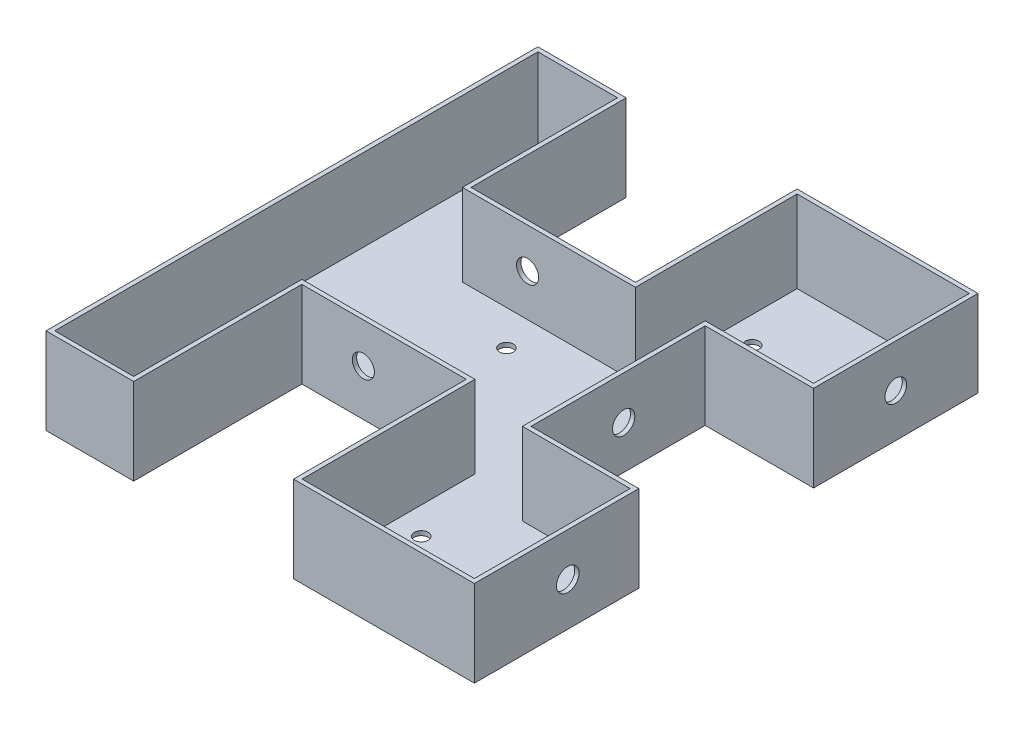
SolidWorks part; units mm, degrees
ref_plane "Front Plane" through (0, 0, 0) normal (0, 0, 1) x (1, 0, 0)
ref_plane "Top Plane" through (0, 0, 0) normal (0, 1, 0) x (1, 0, 0)
ref_plane "Right Plane" through (0, 0, 0) normal (1, 0, 0) x (0, 0, -1)
sketch "Sketch1" plane through (0, 0, 0) normal (0, 1, 0) x (1, 0, 0)
  line L0 (543.0661, -1022.739) -> (543.0661, -1018.5177)
  line L1 (574.7353, -1103.2077) -> (586.3832, -1103.2077) construction
  line L2 (543.0661, -1018.5177) -> (584.9761, -1018.5177)
  line L5 (584.9761, -1056.6177) -> (584.9761, -1018.5177)
  line L6 (559.8652, -1056.6177) -> (584.9761, -1056.6177)
  line L7 (584.8424, -1103.2077) -> (584.8424, -1096.9737)
  line L9 (584.8424, -1096.9737) -> (559.8652, -1096.9737)
  line L10 (559.8652, -1096.9737) -> (559.8652, -1056.6177)
  line L11 (584.8424, -1103.2077) -> (584.8424, -1135.0737)
  line L12 (542.9324, -1128.2718) -> (542.9324, -1135.0737)
  line L14 (542.9324, -1135.0737) -> (584.8424, -1135.0737)
  line L15 (542.9324, -1128.2718) -> (542.9324, -1095.0332)
  line L16 (542.9324, -1095.0332) -> (504.8324, -1095.0332)
  line L17 (504.8324, -1095.0332) -> (504.8324, -1128.2718)
  line L18 (504.8324, -1128.2718) -> (504.8324, -1133.9991)
  line L20 (504.8324, -1133.9991) -> (484.5124, -1133.9991)
  line L21 (484.5124, -1133.9991) -> (484.5124, -1020.0236)
  line L23 (504.9661, -1022.739) -> (504.9661, -1020.0236)
  line L24 (484.5124, -1020.0236) -> (504.9661, -1020.0236)
  line L25 (543.0661, -1022.739) -> (543.0661, -1055.9777)
  line L26 (543.0661, -1055.9777) -> (504.9661, -1055.9777)
  line L27 (504.9661, -1022.739) -> (504.9661, -1055.9777)
  point P2 (572.4206, -1056.6177)
  point P3 (504.9661, -1039.3584)
  point P4 (494.6724, -1133.9991)
  point P5 (523.8824, -1095.0332)
  point P7 (584.8424, -1103.2077)
  point P11 (504.9661, -1020.0236)
  dimension "D3" = 41.91
  dimension "D4" = 41.91
  dimension "D5" = 38.1
  dimension "D6" = 38.1
  dimension "D7" = 38.1
  dimension "D8" = 38.1
  dimension "D9" = 113.9755
  dimension "D10" = 20.32
  dimension "D11" = 37.46
  dimension "D12" = 39.0555
extrude "Boss-Extrude2" add sketch "Sketch1" along normal blind 20 contours L6 L10 L9 L7 L11 L14 L12 L15 L16 L17 L18 L20 L21 L24 L23 L27 L26 L25 L0 L2 L5
shell "Shell1" thickness 1
sketch "Sketch5" plane through (0, 0, 1095.0332) normal (0, 0, 1) x (1, 0, 0)
  circle A0 centre (519.0776, 10.7438) radius 2.5545
extrude "Cut-Extrude1" cut sketch "Sketch5" against normal blind 40.64 contours A0
sketch "Sketch6" plane through (584.9761, 0, 0) normal (1, 0, 0) x (0, 0, -1)
  circle A0 centre (-1037.5677, 10) radius 2.511
  circle A1 centre (-1075.5054, 10) radius 2.5732
  circle A3 centre (-1113.4432, 10) radius 2.5648
extrude "Cut-Extrude3" cut sketch "Sketch6" against normal blind 10 contours A3 | A1 | A0
sketch "Sketch7" plane through (559.8652, 0, 0) normal (1, 0, 0) x (0, 0, -1)
  circle A0 centre (-1075.5054, 10) radius 2.5829
extrude "Cut-Extrude4" cut sketch "Sketch7" against normal blind 10 contours A0
sketch "Sketch8" plane through (584.8424, 0, 0) normal (1, 0, 0) x (0, 0, -1)
  circle A0 centre (-1113.4432, 10) radius 2.6197
sketch "Sketch9" plane through (584.8424, 0, 0) normal (1, 0, 0) x (0, 0, -1)
  circle A0 centre (-1113.4432, 10) radius 2.6197
extrude "Cut-Extrude6" cut sketch "Sketch9" against normal blind 10 contours A0
sketch "Sketch10" plane through (0, 1, 0) normal (0, 1, 0) x (1, 0, 0)
  circle A0 centre (494.0237, -1036.0675) radius 1.6
  circle A1 centre (494.9476, -1112.7632) radius 1.6
  circle A3 centre (550.2052, -1036.0675) radius 1.6
  circle A4 centre (550.2052, -1112.7632) radius 1.6
  circle A6 centre (522.3097, -1065.1025) radius 1.6
  circle A7 centre (522.3097, -1084.7323) radius 1.6
  dimension "D1" = 3.2
  dimension "D2" = 3.2
  dimension "D3" = 3.2
  dimension "D4" = 3.2
  dimension "D5" = 3.2
  dimension "D6" = 3.2
extrude "Cut-Extrude7" cut sketch "Sketch10" against normal blind 10 contours A1 | A4 | A7 | A6 | A3 | A0
